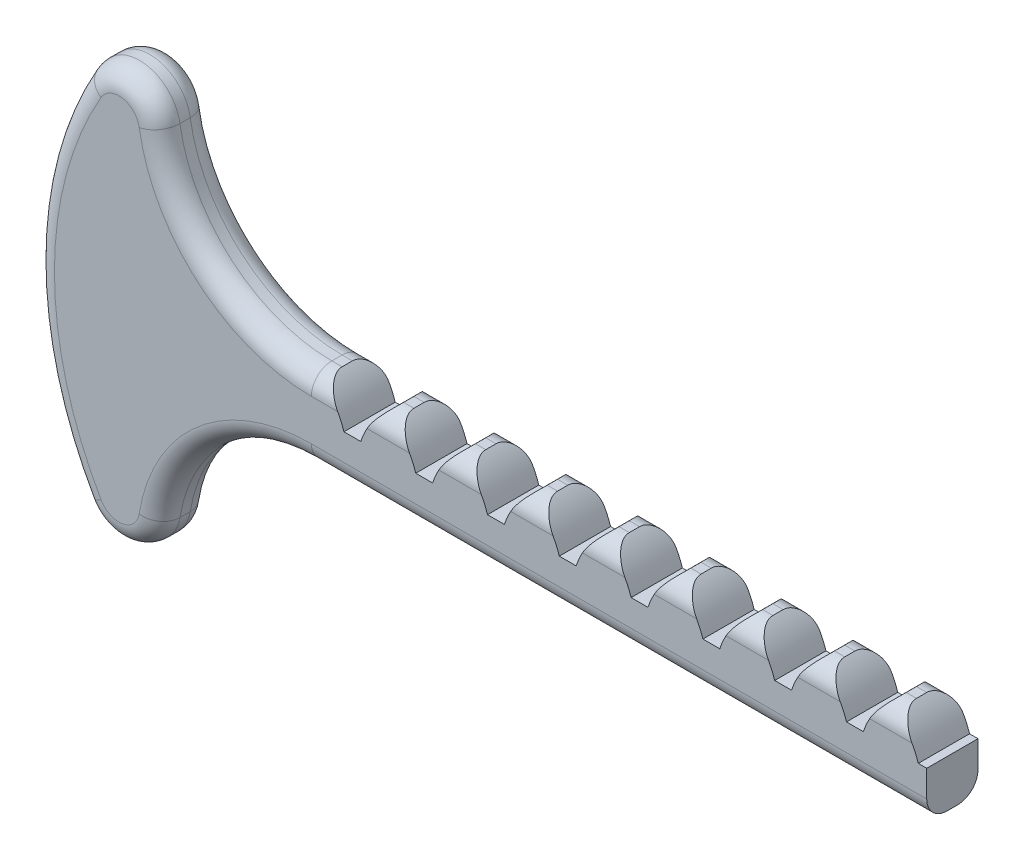
SolidWorks part; units mm, degrees
material "Plain Carbon Steel"
ref_plane "Front Plane" through (0, 0, 0) normal (0, 0, 1) x (1, 0, 0)
ref_plane "Top Plane" through (0, 0, 0) normal (0, 1, 0) x (1, 0, 0)
ref_plane "Right Plane" through (0, 0, 0) normal (1, 0, 0) x (0, 0, -1)
sketch "Sketch1" plane through (0, 0, 0) normal (0, 0, 1) x (1, 0, 0)
  line L0 (-38.1, 0) -> (38.1, 0)
  line L1 (38.1, 0) -> (33.02, 5.08)
  line L2 (33.02, 5.08) -> (-38.1, 5.08)
  arc A0 (-38.1, 5.08) -> (-47.5055, 13.1011) centre (-38.1, 14.605) cw
  arc A2 (-47.5055, -8.0211) -> (-38.1, 0) centre (-38.1, -9.525) cw
  arc A4 (-52.2134, 13.97) -> (-52.2134, -8.89) centre (-32.416, 2.54) ccw
  arc A5 (-52.2134, -8.89) -> (-47.5055, -8.0211) centre (-50.0137, -7.62) ccw
  arc A6 (-47.5055, 13.1011) -> (-52.2134, 13.97) centre (-50.0137, 12.7) ccw
  point P10 (0, 0)
  point P14 (35.56, 2.54)
  point P16 (0, 0)
  dimension "D1" = 45
  dimension "D2" = 5.08
  dimension "D4" = 2.54
  dimension "D5" = 9.525
  dimension "D6" = 22.86
  dimension "D7" = 25.4
  dimension "D3" = 76.2
extrude "Boss-Extrude1" add sketch "Sketch1" along normal mid plane 3.175
fillet "Fillet1" radius 1.27 14 edges at (-2.54, 5.08, 1.5875) (0, 0, 1.5875) (-44.2806, -2.2776, 1.5875) (-49.5526, -10.1178, 1.5875) (-55.276, 2.54, 1.5875) (-49.5526, 15.1978, 1.5875) (0, 0, -1.5875) (-2.54, 5.08, -1.5875) (-44.2806, 7.3576, -1.5875) (-49.5526, 15.1978, -1.5875) (-55.276, 2.54, -1.5875) (-49.5526, -10.1178, -1.5875) (-44.2806, -2.2776, -1.5875) (-44.2806, 7.3576, 1.5875)
sketch "Sketch3" plane through (0, 0, 0) normal (0, 0, 1) x (1, 0, 0)
  line L0 (-38.1, 5.08) -> (33.02, 5.08) construction
  line L1 (30.5929, 2.921) -> (31.6371, 2.921)
  line L2 (29.21, 5.08) -> (33.02, 5.08)
  line L3 (31.115, 5.08) -> (31.115, 2.921) construction
  arc A0 (33.02, 5.08) -> (31.6371, 2.921) centre (36.4678, 1.3492) ccw
  arc A1 (29.21, 5.08) -> (30.5929, 2.921) centre (25.7622, 1.3492) cw
  point P7 (31.115, 3.2312)
  dimension "D1" = 5.08
  dimension "D2" = 2.159
  dimension "D3" = 3.81
  dimension "D4" = 1.0442
extrude "Cut-Extrude1" cut sketch "Sketch3" against normal through all both and the other way through all
pattern_linear "LPattern1" count 16 spacing 4.445 along (-1, 0, 0) of "Cut-Extrude1"
sketch "Sketch4" plane through (0, 0, 0) normal (1, 0, 0) x (0, 0, -1)
  circle A0 centre (0, 0) radius 7.6861
  dimension "D1" = 15.3722
extrude "Cut-Extrude2" cut sketch "Sketch4" along normal through all
